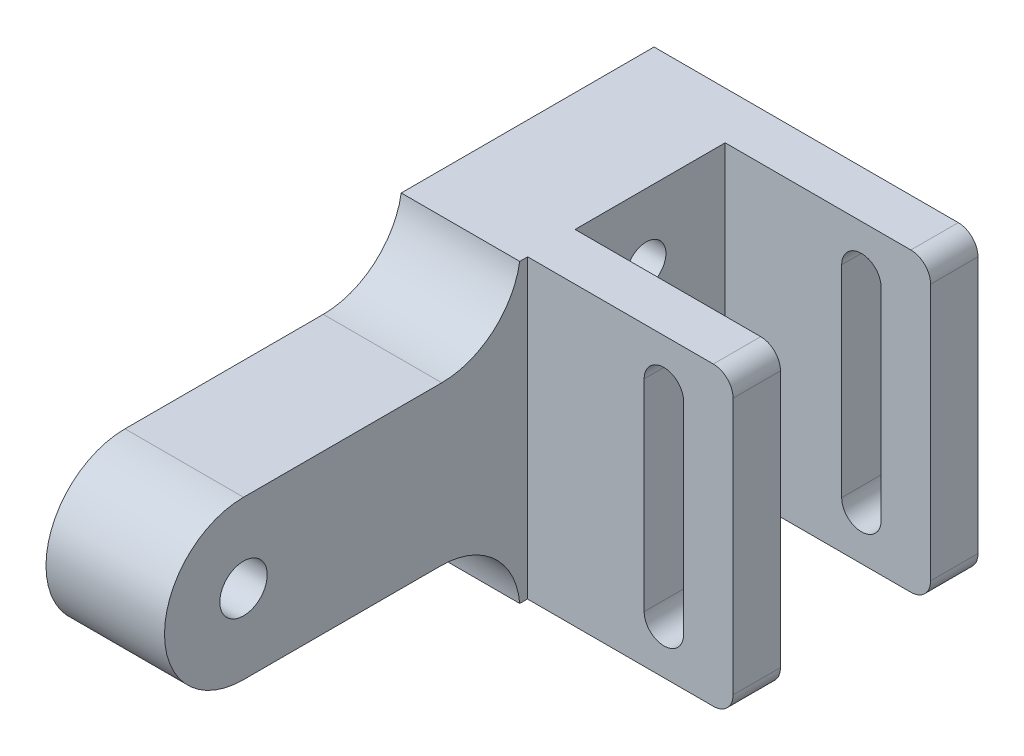
SolidWorks part; units mm, degrees
ref_plane "Front Plane" through (0, 0, 0) normal (0, 0, 1) x (1, 0, 0)
ref_plane "Top Plane" through (0, 0, 0) normal (0, 1, 0) x (1, 0, 0)
ref_plane "Right Plane" through (0, 0, 0) normal (1, 0, 0) x (0, 0, -1)
sketch "Sketch2" plane through (0, 0, 0) normal (1, 0, 0) x (0, 0, -1)
  line L0 (-101.9238, 20.7557) -> (-51.7332, 20.7557)
  line L1 (-32, 37.5) -> (32, 37.5)
  line L3 (-32, -37.5) -> (32, -37.5)
  line L4 (32, 37.5) -> (32, -37.5)
  line L5 (-32, 37.5) -> (32, -37.5) construction
  line L6 (-32, -37.5) -> (32, 37.5) construction
  line L7 (-101.9238, -19.2443) -> (-51.9238, -19.2443)
  arc A0 (-101.9238, 20.7557) -> (-101.9238, -19.2443) centre (-101.9238, 0.7557) ccw
  circle A1 centre (-101.9238, 0.7557) radius 6
  arc A2 (-51.7332, 20.7557) -> (-32, 37.5) centre (-51.7332, 40.7557) ccw
  arc A3 (-51.9238, -19.2443) -> (-32, -37.5) centre (-51.9238, -39.2443) cw
  circle A4 centre (0, 20.7557) radius 5
  circle A5 centre (0, -16.6964) radius 5
  point P0 (0, 0)
  dimension "D1" = 12
  dimension "D2" = 40
  dimension "D3" = 20
  dimension "D4" = 20
  dimension "D8" = 10
  dimension "D9" = 10
  dimension "D5" = 64
  dimension "D6" = 75
  dimension "D7" = 50
extrude "Boss-Extrude3" add sketch "Sketch2" along normal blind 30
sketch "Sketch4" plane through (0, 0, -32) normal (0, 0, -1) x (-1, 0, 0)
  line L0 (-64.4908, 25.5) -> (-64.4908, -25.5433) construction
  line L1 (-30, 37.5) -> (-77, 37.5)
  line L2 (-30, 37.5) -> (-30, -37.5433)
  line L3 (-30, -37.5433) -> (-77, -37.5433)
  line L4 (-82, 32.5) -> (-82, -32.5433)
  line L5 (-59.4908, 25.5) -> (-59.4908, -25.5433)
  line L6 (-69.4908, 25.5) -> (-69.4908, -25.5433)
  arc A0 (-77, -37.5433) -> (-82, -32.5433) centre (-77, -32.5433) cw
  arc A1 (-77, 37.5) -> (-82, 32.5) centre (-77, 32.5) ccw
  arc A2 (-59.4908, 25.5) -> (-69.4908, 25.5) centre (-64.4908, 25.5) ccw
  arc A3 (-69.4908, -25.5433) -> (-59.4908, -25.5433) centre (-64.4908, -25.5433) ccw
  point P5 (-82, -0.0217)
  point P10 (-82, 37.5)
  point P13 (-64.4908, -0.0217)
  point P18 (-64.4908, 30.5)
  dimension "D3" = 5
  dimension "D4" = 5
  dimension "D5" = 5
  dimension "D6" = 12
  dimension "D1" = 37.5217
  dimension "D2" = 52
  dimension "D7" = 7
extrude "Boss-Extrude6" add sketch "Sketch4" against normal blind 12
pattern_linear "LPattern1" count 2 spacing 50 along (0, 0, 1) of "Boss-Extrude6"
